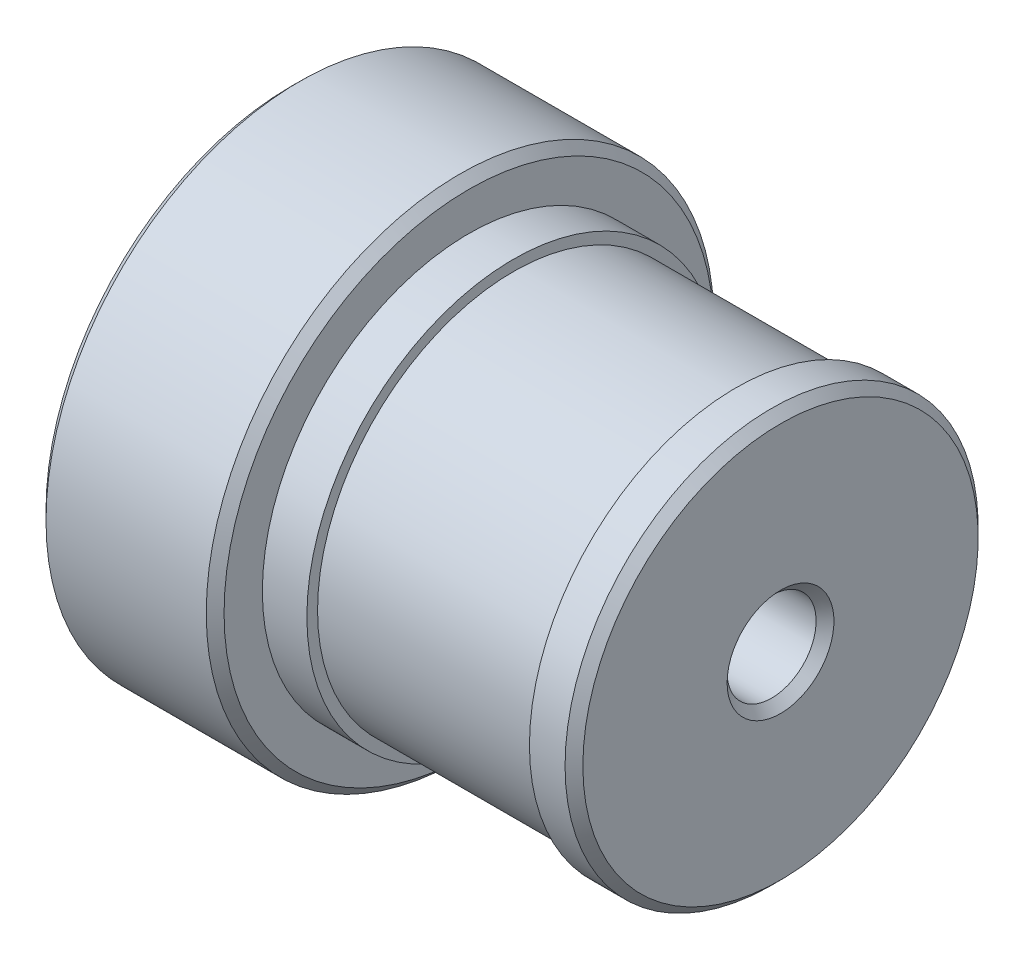
SolidWorks part; units mm, degrees
material "Сталь 40Х ГОСТ 4543-71"
ref_plane "Спереди (Плоскость XY)" through (0, 0, 0) normal (0, 0, 1) x (1, 0, 0)
ref_plane "Сверху (Плоскость XZ)" through (0, 0, 0) normal (0, 1, 0) x (1, 0, 0)
ref_plane "Справа (Плоскость ZY)" through (0, 0, 0) normal (1, 0, 0) x (0, 0, -1)
other "Configuration Table"
sketch "Эскиз1" plane through (0, 0, 0) normal (0, 0, 1) x (1, 0, 0)
  line L0 (0, 0) -> (154.849, 0) construction
  line L1 (0, 5) -> (0, 28.5)
  line L2 (20, 23.2) -> (25, 23.2)
  line L3 (55, 23.2) -> (55, 5)
  line L5 (20, 23.2) -> (20, 28.5)
  line L6 (20, 28.5) -> (0, 28.5)
  line L8 (0, 5) -> (55, 5)
  line L9 (25, 23.2) -> (25, 22)
  line L10 (25, 22) -> (50, 22)
  line L11 (50, 22) -> (50, 23.2)
  line L12 (50, 23.2) -> (55, 23.2)
  dimension "D4" = 57
  dimension "D1" = 46.4
  dimension "D2" = 55
  dimension "D3" = 20
  dimension "D5" = 10
  dimension "D6" = 5
  dimension "D7" = 5
  dimension "D8" = 44
revolve "Повернуть1" add sketch "Эскиз1" angle 360 about L0
chamfer "Фаска4" distance 1 angle 45 5 edges at (55, 0, 5) (55, 0, 23.2) (20, 0, 28.5) (0, 0, 5) (0, 0, 28.5)
